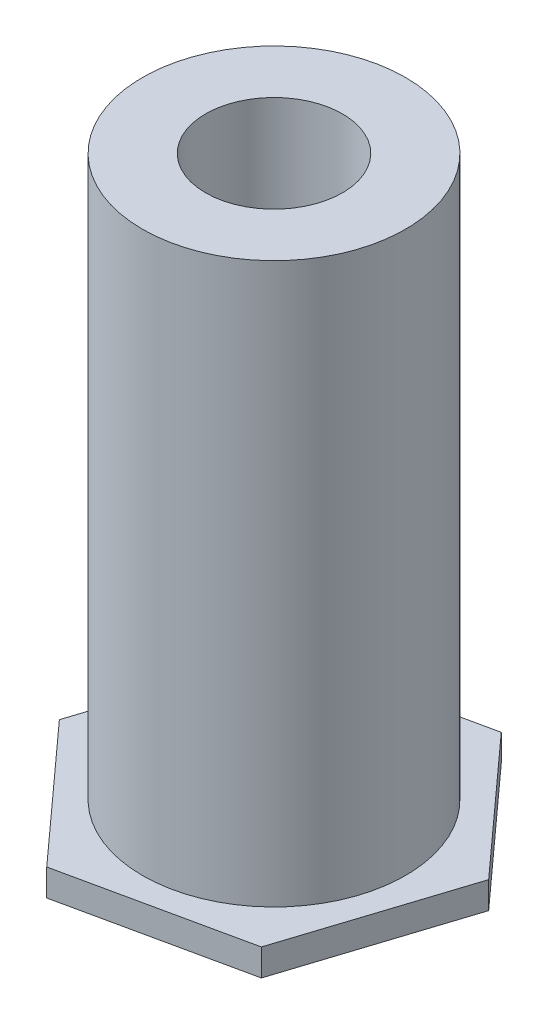
SolidWorks part; units mm, degrees
ref_plane "Plano frontal" through (0, 0, 0) normal (0, 0, 1) x (1, 0, 0)
ref_plane "Plano superior" through (0, 0, 0) normal (0, 1, 0) x (1, 0, 0)
ref_plane "Plano direito" through (0, 0, 0) normal (1, 0, 0) x (0, 0, -1)
sketch "Esboço1" plane through (0, 0, 0) normal (0, 1, 0) x (1, 0, 0)
  line L1 (2.4804, -2.7388) -> (3.6121, 0.7787)
  line L2 (3.6121, 0.7787) -> (1.1317, 3.5175)
  line L3 (1.1317, 3.5175) -> (-2.4804, 2.7388)
  line L4 (-2.4804, 2.7388) -> (-3.6121, -0.7787)
  line L5 (-3.6121, -0.7787) -> (-1.1317, -3.5175)
  line L6 (-1.1317, -3.5175) -> (2.4804, -2.7388)
  circle A0 centre (0, 0) radius 3.2 construction
  dimension "D1" = 6.4
extrude "Ressalto-extrusão1" add sketch "Esboço1" along normal blind 0.55
sketch "Esboço2" plane through (0, 0.55, 0) normal (0, 1, 0) x (1, 0, 0)
  circle A0 centre (0, 0) radius 2.69
  circle A1 centre (0, 0) radius 1.4
  dimension "D1" = 5.38
extrude "Ressalto-extrusão2" add sketch "Esboço2" along normal blind 11.45
